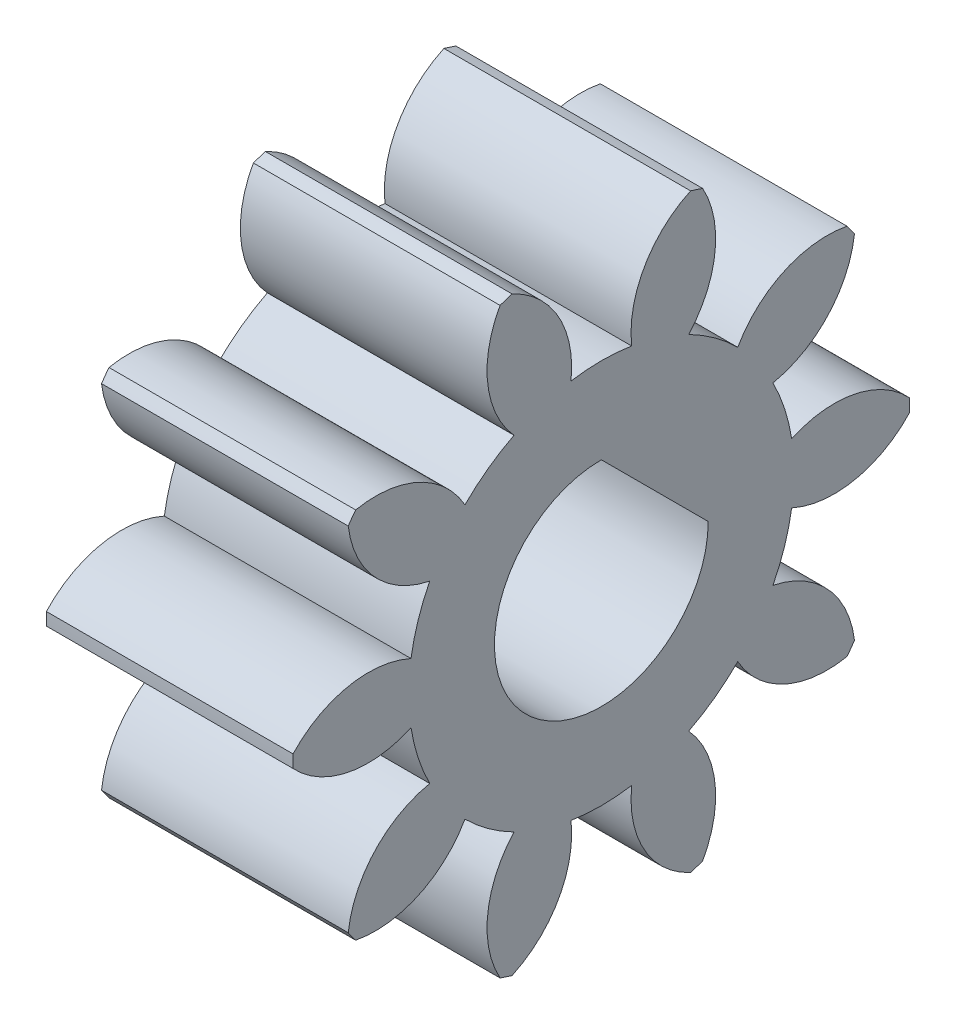
SolidWorks part; units mm, degrees
ref_plane "Plane1" through (0, 0, 0) normal (0, 0, 1) x (1, 0, 0)
ref_plane "Plane2" through (0, 0, 0) normal (0, 1, 0) x (1, 0, 0)
ref_plane "Plane3" through (0, 0, 0) normal (1, 0, 0) x (0, 0, -1)
other "Configuration Table"
sketch "HoldingSke" plane through (0, 0, 0) normal (0, 1, 0) x (1, 0, 0)
  line L0 (0, 0) -> (0.7878, -0.1389)
  line L1 (-15, 0) -> (100, 0) construction
  line L2 (0, 0) -> (-2.1039, 2.3779)
  line L3 (0, 0) -> (-11.863, 4.5341)
  line L4 (0, 0) -> (8.5048, 1.4996)
  line L5 (0, 0) -> (-46.8476, -17.4728)
  line L6 (0, 0) -> (-4.9738, -3.3558)
  line L7 (-2.1039, 2.3779) -> (8.6586, 51.2059)
  line L8 (-76.2, 54.61) -> (-75.3, 54.61)
  line L9 (-71.009, 38.7566) -> (-53.1078, 45.2721)
  line L10 (-76.2, 71.12) -> (104.1128, 71.12)
  line L11 (0, 0) -> (-6, 0)
  line L12 (-76.2, 101.6) -> (-76.155, 101.6)
  line L13 (24.9733, 27.94) -> (52.9518, 28.4284)
  line L14 (24.9733, 27.94) -> (24.9743, 27.94)
  line L15 (24.9733, 27.94) -> (100.4006, 29.5858)
  line L16 (-63.627, -1.25) -> (-12.827, -1.25)
  circle A0 centre (0, 0) radius 2.5
  circle A1 centre (0, 0) radius 4.6865
  circle A2 centre (0, 0) radius 37.5
  circle A3 centre (0, 0) radius 2.5
  dimension "MHD" = 9.373
  dimension "Hub_dia" = 75
  dimension "Bore" = 5
  dimension "MBD" = 5
  dimension "Num_teeth" = 10
  dimension "Pitch" = 0.8
  dimension "Overall_len" = 50
  dimension "Show_teeth" = 10
  dimension "Thickness" = 6
  dimension "OAL" = 50.0001
  dimension "T_dim" = 0.9
  dimension "Ap" = 20
  dimension "H" = 19.05
  dimension "Pitch_radius" = 180.3128
  dimension "Width" = 6
  dimension "Backlash" = 0.045
  dimension "Addendum_fac" = 1
  dimension "Dedendum_fac" = 1.25
  dimension "Clearance_fac" = 0.25
  dimension "Dedendum_add" = 0.001
  dimension "Module" = 1.25
sketch "BasProSke" plane through (0, 0, 0) normal (0, 1, 0) x (1, 0, 0)
  line L0 (-10, 0) -> (60, 0) construction
  line L1 (0, 0) -> (0, 7.5)
  line L2 (0, 0) -> (6, 0)
  line L3 (6, 0) -> (6, 7.5)
  line L4 (6, 7.5) -> (0, 7.5)
  dimension "Thickness" = 6
  dimension "Diameter" = 15
revolve "Base-Revolve" add sketch "BasProSke" angle 360 about L0
sketch "TooCutSke" plane through (0, 0, 0) normal (1, 0, 0) x (0, 0, -1)
  line L1 (0, 0) -> (0, 107) construction
  line L2 (0, 0) -> (-1.0563, 6.1601) construction
  line L3 (0, 0) -> (-3.8225, 11.7646) construction
  line L4 (-1.0563, 6.1601) -> (-1.9113, 5.8823) construction
  arc A0 (0.7377, 4.6281) -> (-0.7377, 4.6281) centre (0, 0) ccw
  arc A1 (2.2058, 7.1949) -> (-2.2058, 7.1949) centre (0, 0) ccw
  circle A2 centre (0, 0) radius 6.25 construction
  circle A3 centre (0, 0) radius 5.8731 construction
  arc A4 (-0.7377, 4.6281) -> (-2.2058, 7.1949) centre (-3.2217, 4.9106) ccw
  arc A5 (2.2058, 7.1949) -> (0.7377, 4.6281) centre (3.2217, 4.9106) ccw
  dimension "Root_dia" = 9.373
  dimension "Overcut_dia" = 15.0508
  dimension "Pitch_dia" = 12.5
  dimension "Base_dia" = 11.7462
  dimension "Flank_rad" = 2.5
  dimension "Half_ang" = 18
  dimension "Half_CT" = 0.899
extrude "ToothCut" cut sketch "TooCutSke" along normal through all
fillet "Breaks" [suppressed] radius 0.025
fillet "RootFillets" [suppressed] radius 0.3135
pattern_circular "TeethCuts" count 10 every 36 about axis through (-10, 0, 0) along (1, 0, 0) of "ToothCut", "RootFillets", "Breaks"
sketch "HubNeaOneSke" plane through (0, 0, 0) normal (-1, 0, 0) x (0, 0, 1)
  circle A0 centre (0, 0) radius 4.6865
  dimension "Diameter" = 9.373
extrude "HubNearOne" [suppressed] add sketch "HubNeaOneSke" along normal blind 44.0001
sketch "HubNeaBotSke" plane through (0, 0, 0) normal (-1, 0, 0) x (0, 0, 1)
  circle A0 centre (0, 0) radius 4.6865
  dimension "Diameter" = 9.373
extrude "HubNearBoth" [suppressed] add sketch "HubNeaBotSke" along normal blind 22
ref_plane "FarPln" through (6, 0, 0) normal (1, 0, 0) x (0, 0, -1)
sketch "HubFarSke" plane through (6, 0, 0) normal (1, 0, 0) x (0, 0, -1)
  circle A0 centre (0, 0) radius 4.6865
  dimension "Diameter" = 9.373
extrude "HubFar" [suppressed] add sketch "HubFarSke" along normal blind 22
sketch "BorSke" plane through (0, 0, 0) normal (1, 0, 0) x (0, 0, -1)
  circle A0 centre (0, 0) radius 2.5
  dimension "Diameter" = 5
extrude "Bore" cut sketch "BorSke" along normal mid plane 100.0001
sketch "KeySke" plane through (0, 0, 0) normal (1, 0, 0) x (0, 0, -1)
  line L0 (-1, 0) -> (-1, 3.4)
  line L1 (-1, 3.4) -> (1, 3.4)
  line L2 (1, 3.4) -> (1, 0)
  line L3 (0, 0) -> (0, 34) construction
  line L4 (-1, 0) -> (1, 0)
  dimension "Offset" = 3.4
  dimension "Width" = 2
extrude "Keyway" [suppressed] cut sketch "KeySke" along normal mid plane 100.0001
pattern_circular "Keyway2" [suppressed] count 2 every 90 about axis through (-10, 0, 0) along (1, 0, 0)
sketch "Sketch1" plane through (6, 0, 0) normal (1, 0, 0) x (0, 0, -1)
  circle A0 centre (0, 0) radius 2.6
  dimension "D1" = 5.2
extrude "Cut-Extrude1" cut sketch "Sketch1" against normal through all
sketch "Sketch2" plane through (6, 0, 0) normal (1, 0, 0) x (0, 0, -1)
  line L0 (0, 0) -> (2.6, 0) construction
  line L1 (0, 0) -> (0, 2.6) construction
  line L2 (0, 2.6) -> (2.6, 0)
  line L3 (2.6, 0) -> (2.6, 2.6)
  line L4 (2.6, 2.6) -> (0, 2.6)
  circle A0 centre (0, 0) radius 2.6 construction
extrude "Boss-Extrude1" add sketch "Sketch2" against normal up to surface (6 mm away) from surface at 0 up to face at (0, 0, -2.6) starting at face at (6, 0, -2.6)
equation "' \"Module@HoldingSke\" = 6.35"
equation "' \"Num_teeth@HoldingSke\" = 12"
equation "' \"Ap@HoldingSke\" =  20"
equation "' \"Ap@HoldingSke\" = 20"
equation "' \"Width@HoldingSke\" = 0.5 * 25.4"
equation "' \"Hub_dia@HoldingSke\"= 1 * 25.4"
equation "' \"Hub_dia@HoldingSke\" = 1 * 25.4"
equation "' \"Overall_len@HoldingSke\" = 1.0 * 25.4"
equation "' \"Bore@HoldingSke\" = 0.75 * 25.4"
equation "' \"T_dim@HoldingSke\" = 0.1 * 25.4"
equation "' \"Width@KeySke\" = 0.25 * 25.4"
equation "' \"Show_teeth@HoldingSke\" = 13"
equation "' \"Backlash@HoldingSke\" = 0.009 * 25.4"
equation "' \"Addendum_fac@HoldingSke\" = 1.0"
equation "' \"Dedendum_fac@HoldingSke\" = 1.25"
equation "' \"Dedendum_add@HoldingSke\" = 0.00005 * 25.4"
equation "' \"Clearance_fac@HoldingSke\" = 0.25"
equation "\"Pitch@HoldingSke\" = 1 / \"Module@HoldingSke\""
equation "\"Overcut_dia@TooCutSke\" = (\"Num_teeth@HoldingSke\" + 2 * \"Addendum_fac@HoldingSke\") / \"Pitch@HoldingSke\" + 0.002 * 25.4"
equation "\"Pitch_dia@TooCutSke\" = \"Num_teeth@HoldingSke\" / \"Pitch@HoldingSke\""
equation "\"Base_dia@TooCutSke\" = \"Num_teeth@HoldingSke\" / \"Pitch@HoldingSke\" * cos((\"Ap@HoldingSke\"  * 3.14159265 / 180))"
equation "\"Root_dia@TooCutSke\" = (\"Num_teeth@HoldingSke\" + 2) / \"Pitch@HoldingSke\" - 2 * (\"Addendum_fac@HoldingSke\" + \"Dedendum_fac@HoldingSke\") / \"Pitch@HoldingSke\" - \"Dedendum_add@HoldingSke\" * 2"
equation "\"Half_ang@TooCutSke\" = 180 / \"Num_teeth@HoldingSke\""
equation "\"Half_CT@TooCutSke\" = \"Num_teeth@HoldingSke\" / \"Pitch@HoldingSke\" * sin((3.14159265 / 2 / \"Num_teeth@HoldingSke\")) / 2 - 7 * \"Backlash@HoldingSke\" / 4"
equation "\"Flank_rad@TooCutSke\" = \"Num_teeth@HoldingSke\" / \"Pitch@HoldingSke\" / 5"
equation "\"Radius@RootFillets\" = \"Clearance_fac@HoldingSke\" / \"Pitch@HoldingSke\" + \"Dedendum_add@HoldingSke\""
equation "\"Break_rad@Breaks\" = 0.02 / \"Pitch@HoldingSke\""
equation "\"Thickness@HoldingSke\" = \"Width@HoldingSke\""
equation "\"OAL@HoldingSke\" = \"Thickness@HoldingSke\""
equation "\"MHD@HoldingSke\" = (\"Num_teeth@HoldingSke\" + 2) / \"Pitch@HoldingSke\" - 2 * (\"Addendum_fac@HoldingSke\" + \"Dedendum_fac@HoldingSke\")  / \"Pitch@HoldingSke\" - \"Dedendum_add@HoldingSke\" * 2"
equation "\"MBD@HoldingSke\" = (\"Num_teeth@HoldingSke\" + 2) / \"Pitch@HoldingSke\" - 2 * (\"Addendum_fac@HoldingSke\" + \"Dedendum_fac@HoldingSke\")  / \"Pitch@HoldingSke\" - \"Dedendum_add@HoldingSke\" * 2 - 0.002 * 25.4"
equation "\"MHD@HoldingSke\" = ((sgn( \"MHD@HoldingSke\" - \"Hub_dia@HoldingSke\" )-1)*( \"MHD@HoldingSke\" - \"Hub_dia@HoldingSke\" ))/-2+ \"Hub_dia@HoldingSke\""
equation "\"MBD@HoldingSke\" = ((sgn( \"MBD@HoldingSke\" - \"Bore@HoldingSke\" )-1)*( \"MBD@HoldingSke\" - \"Bore@HoldingSke\" ))/-2+ \"Bore@HoldingSke\""
equation "\"OAL@HoldingSke\" = ((sgn( \"OAL@HoldingSke\" - \"Overall_len@HoldingSke\" )+1)*( \"OAL@HoldingSke\" - \"Overall_len@HoldingSke\" ))/2 + \"Overall_len@HoldingSke\" + 0.000002 * 25.4"
equation "\"Num_teeth@TeethCuts\" = int( \"Show_teeth@HoldingSke\" ) + 1"
equation "\"Num_teeth@TeethCuts\" = ((sgn( \"Num_teeth@TeethCuts\" - \"Num_teeth@HoldingSke\" )-1)*( \"Num_teeth@TeethCuts\" - \"Num_teeth@HoldingSke\" ))/-2+ \"Num_teeth@HoldingSke\""
equation "\"Num_teeth@TeethCuts\" = ((sgn( \"Num_teeth@TeethCuts\" - 2.0)+1)*( \"Num_teeth@TeethCuts\" - 2.0))/2 +2.0"
equation "\"Angle@TeethCuts\" = 360.0 / \"Num_teeth@HoldingSke\""
equation "\"Diameter@BasProSke\" = (\"Num_teeth@HoldingSke\" + 2 * \"Addendum_fac@HoldingSke\") / \"Pitch@HoldingSke\""
equation "\"Thickness@BasProSke\"  = \"Thickness@HoldingSke\""
equation "' \"Fillet_rad@BasProSke\" =  \"Thickness@HoldingSke\" * 0.05"
equation "' \"Fillet_rad@BasProSke\" = \"Thickness@HoldingSke\" * 0.05"
equation "\"MHD@HoldingSke\" = ((sgn( \"MHD@HoldingSke\" - \"Root_dia@TooCutSke\" )-1)*( \"MHD@HoldingSke\" - \"Root_dia@TooCutSke\" ))/-2+ \"Root_dia@TooCutSke\""
equation "\"Diameter@HubNeaOneSke\" = \"MHD@HoldingSke\""
equation "\"Length@HubNearOne\" = \"OAL@HoldingSke\" - \"Thickness@BasProSke\""
equation "\"Diameter@HubNeaBotSke\" = \"MHD@HoldingSke\""
equation "\"Length@HubNearBoth\" = ( \"OAL@HoldingSke\" - \"Thickness@BasProSke\" ) / 2.0"
equation "\"Thickness@FarPln\" = \"Thickness@BasProSke\""
equation "\"Diameter@HubFarSke\" = \"MHD@HoldingSke\""
equation "\"Length@HubFar\" = ( \"OAL@HoldingSke\" - \"Thickness@BasProSke\" ) / 2.0"
equation "\"Diameter@BorSke\" = \"MBD@HoldingSke\""
equation "\"D1@Bore\" = \"OAL@HoldingSke\" * 2.0"
equation "\"D1@Keyway\" = \"OAL@HoldingSke\" * 2.0"
equation "\"Offset@KeySke\" = \"T_dim@HoldingSke\" + \"MBD@HoldingSke\" / 2.0"
